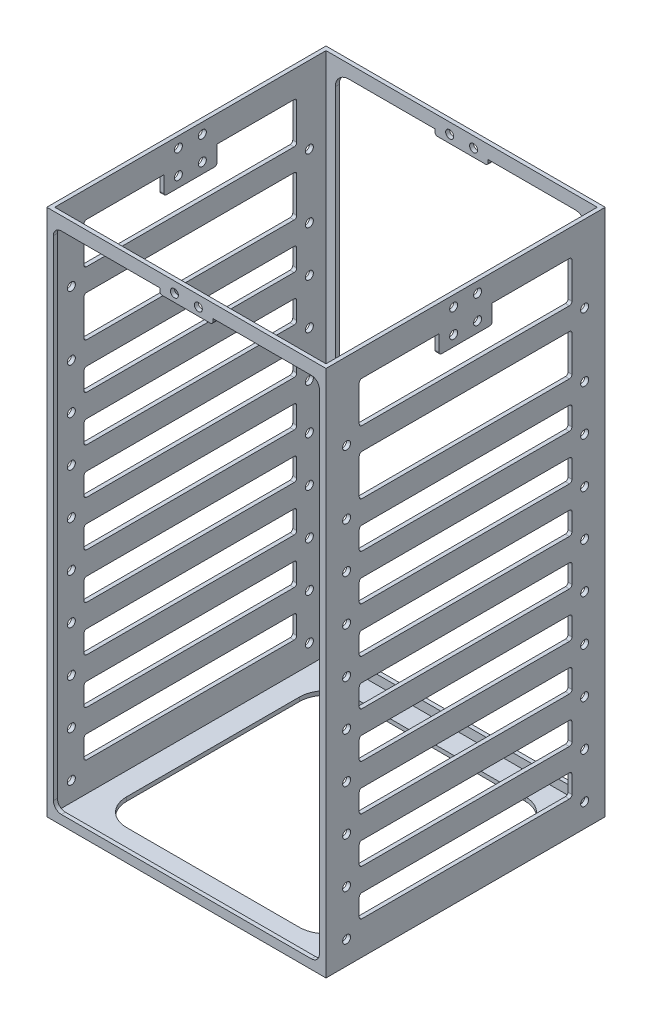
SolidWorks part; units mm, degrees
ref_plane "Front Plane" through (0, 0, 0) normal (0, 0, 1) x (1, 0, 0)
ref_plane "Top Plane" through (0, 0, 0) normal (0, 1, 0) x (1, 0, 0)
ref_plane "Right Plane" through (0, 0, 0) normal (1, 0, 0) x (0, 0, -1)
sketch "Sketch1" plane through (0, 0, 0) normal (0, 1, 0) x (1, 0, 0)
  line L1 (-52.5, -52.5) -> (52.5, -52.5)
  line L2 (-52.5, -52.5) -> (-52.5, 52.5)
  line L3 (-52.5, 52.5) -> (52.5, 52.5)
  line L4 (52.5, -52.5) -> (52.5, 52.5)
  line L5 (-52.5, -52.5) -> (52.5, 52.5) construction
  line L6 (-52.5, 52.5) -> (52.5, -52.5) construction
  line L7 (-32.5, -42.5) -> (32.5, -42.5)
  line L8 (-42.5, -32.5) -> (-42.5, 32.5)
  line L9 (-32.5, 42.5) -> (32.5, 42.5)
  line L10 (42.5, -32.5) -> (42.5, 32.5)
  line L11 (-42.5, -42.5) -> (42.5, 42.5) construction
  line L12 (-42.5, 42.5) -> (42.5, -42.5) construction
  arc A0 (32.5, -42.5) -> (42.5, -32.5) centre (32.5, -32.5) ccw
  arc A1 (32.5, 42.5) -> (42.5, 32.5) centre (32.5, 32.5) cw
  arc A2 (-42.5, 32.5) -> (-32.5, 42.5) centre (-32.5, 32.5) cw
  arc A3 (-32.5, -42.5) -> (-42.5, -32.5) centre (-32.5, -32.5) cw
  point P0 (0, 0)
  point P6 (0, 0)
  dimension "D3" = 10
  dimension "D1" = 105
  dimension "D2" = 42.5
extrude "Boss-Extrude2" add sketch "Sketch1" along normal blind 1.5 contours A3 L7 A0 L10 A1 L9 A2 L8 | L2 L1 L4 L3
sketch "Sketch3" plane through (0, 1.5, 0) normal (0, 1, 0) x (1, 0, 0)
  line L1 (-52.5, -52.5) -> (52.5, -52.5)
  line L2 (-52.5, -52.5) -> (-52.5, 52.5)
  line L3 (-52.5, 52.5) -> (52.5, 52.5)
  line L4 (52.5, -52.5) -> (52.5, 52.5)
  line L5 (-52.5, -52.5) -> (52.5, 52.5) construction
  line L6 (-52.5, 52.5) -> (52.5, -52.5) construction
  line L7 (-51, -51) -> (51, -51)
  line L8 (-51, -51) -> (-51, 51)
  line L9 (-51, 51) -> (51, 51)
  line L10 (51, -51) -> (51, 51)
  line L11 (-51, -51) -> (51, 51) construction
  line L12 (-51, 51) -> (51, -51) construction
  point P0 (0, 0)
  point P7 (0, 0)
  dimension "D1" = 1.5
extrude "Boss-Extrude3" add sketch "Sketch3" along normal blind 197 contours L8 L7 L10 L9 | L2 L3 L4 L1
sketch "Sketch4" plane through (0, 0, -52.5) normal (0, 0, 1) x (1, 0, 0)
  line L0 (-52.5, 0) -> (52.5, 0) construction
  line L1 (-42.5, 5) -> (42.5, 5)
  line L2 (-47.5, 10) -> (-47.5, 188.5)
  line L3 (-42.5, 193.5) -> (42.5, 193.5)
  line L4 (47.5, 10) -> (47.5, 188.5)
  line L5 (-47.5, 5) -> (47.5, 193.5) construction
  line L6 (-47.5, 193.5) -> (47.5, 5) construction
  line L7 (52.5, 198.5) -> (52.5, 0) construction
  line L8 (-51, 198.5) -> (51, 198.5) construction
  line L9 (-52.5, 198.5) -> (-52.5, 0) construction
  arc A0 (-42.5, 5) -> (-47.5, 10) centre (-42.5, 10) cw
  arc A1 (42.5, 5) -> (47.5, 10) centre (42.5, 10) ccw
  arc A2 (42.5, 193.5) -> (47.5, 188.5) centre (42.5, 188.5) cw
  arc A3 (-47.5, 188.5) -> (-42.5, 193.5) centre (-42.5, 188.5) cw
  point P0 (0, 99.25)
  dimension "D5" = 5
  dimension "D1" = 5
  dimension "D2" = 5
  dimension "D3" = 5
  dimension "D4" = 5
extrude "Cut-Extrude1" cut sketch "Sketch4" along normal up to surface (1.5 mm away) up to face at (0, 100, -51)
sketch "Sketch5" plane through (0, 0, 52.5) normal (0, 0, 1) x (1, 0, 0)
  line L0 (-52.5, 198.5) -> (52.5, 198.5) construction
  line L1 (-47, 3.5) -> (47, 3.5)
  line L2 (-50, 6.5) -> (-50, 190.5)
  line L3 (-47, 193.5) -> (47, 193.5)
  line L4 (50, 6.5) -> (50, 190.5)
  line L5 (-50, 3.5) -> (50, 193.5) construction
  line L6 (-50, 193.5) -> (50, 3.5) construction
  line L7 (-52.5, 1.5) -> (52.5, 1.5) construction
  line L8 (-52.5, 198.5) -> (-52.5, 0) construction
  line L9 (52.5, 198.5) -> (52.5, 0) construction
  arc A0 (47, 3.5) -> (50, 6.5) centre (47, 6.5) ccw
  arc A1 (-47, 3.5) -> (-50, 6.5) centre (-47, 6.5) cw
  arc A2 (47, 193.5) -> (50, 190.5) centre (47, 190.5) cw
  arc A3 (-50, 190.5) -> (-47, 193.5) centre (-47, 190.5) cw
  point P0 (0, 98.5)
  dimension "D5" = 3
  dimension "D1" = 5
  dimension "D2" = 2
  dimension "D3" = 2.5
  dimension "D4" = 2.5
sketch "Sketch6" plane through (52.5, 0, 0) normal (1, 0, 0) x (0, 0, -1)
  line L0 (-52.5, 3.5) -> (-52.5, 193.5) construction
  line L1 (52.5, 198.5) -> (52.5, 0) construction
  line L2 (-52.5, 0) -> (52.5, 0) construction
  circle A0 centre (-44.75, 8.75) radius 1.5
  circle A1 centre (44.75, 8.75) radius 1.5
  circle A2 centre (-44.75, 25.85) radius 1.5
  circle A3 centre (44.75, 25.85) radius 1.5
  circle A4 centre (-44.75, 42.95) radius 1.5
  circle A5 centre (44.75, 42.95) radius 1.5
  circle A6 centre (-44.75, 60.05) radius 1.5
  circle A7 centre (44.75, 60.05) radius 1.5
  circle A8 centre (-44.75, 77.15) radius 1.5
  circle A9 centre (44.75, 77.15) radius 1.5
  circle A10 centre (-44.75, 94.25) radius 1.5
  circle A11 centre (44.75, 94.25) radius 1.5
  circle A12 centre (-44.75, 111.35) radius 1.5
  circle A13 centre (44.75, 111.35) radius 1.5
  circle A14 centre (-44.75, 128.45) radius 1.5
  circle A15 centre (44.75, 128.45) radius 1.5
  circle A16 centre (-44.75, 145.55) radius 1.5
  circle A17 centre (44.75, 145.55) radius 1.5
  circle A18 centre (-44.75, 169.55) radius 1.5
  circle A19 centre (44.75, 169.55) radius 1.5
  dimension "D4" = 3
  dimension "D5" = 3
  dimension "D1" = 7.75
  dimension "D2" = 7.75
  dimension "D3" = 8.75
  dimension "D7" = 17.1
  dimension "D9" = 24
  dimension "D6" = 9
  dimension "D8" = 2
extrude "Cut-Extrude2" cut sketch "Sketch6" against normal through all
extrude "Cut-Extrude3" cut sketch "Sketch5" against normal up to surface (1.5 mm away) up to face at (0, 100, 51)
sketch "Sketch7" plane through (52.5, 0, 0) normal (1, 0, 0) x (0, 0, -1)
  line L0 (-40, 30.65) -> (-40, 37.15)
  line L1 (-39, 12.55) -> (39, 12.55)
  line L2 (-40, 13.55) -> (-40, 20.05)
  line L3 (-39, 21.05) -> (39, 21.05)
  line L4 (40, 13.55) -> (40, 20.05)
  line L5 (-40, 12.55) -> (40, 21.05) construction
  line L6 (-40, 21.05) -> (40, 12.55) construction
  line L7 (52.5, 198.5) -> (52.5, 0) construction
  line L8 (-39, 29.65) -> (39, 29.65)
  line L9 (40, 30.65) -> (40, 37.15)
  line L10 (-39, 38.15) -> (39, 38.15)
  line L11 (-40, 47.75) -> (-40, 54.25)
  line L12 (-39, 46.75) -> (39, 46.75)
  line L13 (40, 47.75) -> (40, 54.25)
  line L14 (-39, 55.25) -> (39, 55.25)
  line L15 (-40, 64.85) -> (-40, 71.35)
  line L16 (-39, 63.85) -> (39, 63.85)
  line L17 (40, 64.85) -> (40, 71.35)
  line L18 (-39, 72.35) -> (39, 72.35)
  line L19 (-40, 81.95) -> (-40, 88.45)
  line L20 (-39, 80.95) -> (39, 80.95)
  line L21 (40, 81.95) -> (40, 88.45)
  line L22 (-39, 89.45) -> (39, 89.45)
  line L23 (-40, 99.05) -> (-40, 105.55)
  line L24 (-39, 98.05) -> (39, 98.05)
  line L25 (40, 99.05) -> (40, 105.55)
  line L26 (-39, 106.55) -> (39, 106.55)
  line L27 (-40, 116.15) -> (-40, 122.65)
  line L28 (-39, 115.15) -> (39, 115.15)
  line L29 (40, 116.15) -> (40, 122.65)
  line L30 (-39, 123.65) -> (39, 123.65)
  line L31 (-40, 133.25) -> (-40, 139.75)
  line L32 (-39, 132.25) -> (39, 132.25)
  line L33 (40, 133.25) -> (40, 139.75)
  line L34 (-39, 140.75) -> (39, 140.75)
  circle A0 centre (-44.75, 8.75) radius 1.5 construction
  arc A1 (39, 21.05) -> (40, 20.05) centre (39, 20.05) cw
  arc A2 (39, 12.55) -> (40, 13.55) centre (39, 13.55) ccw
  arc A3 (-39, 12.55) -> (-40, 13.55) centre (-39, 13.55) cw
  arc A4 (-40, 20.05) -> (-39, 21.05) centre (-39, 20.05) cw
  arc A5 (-40, 37.15) -> (-39, 38.15) centre (-39, 37.15) cw
  arc A6 (-39, 29.65) -> (-40, 30.65) centre (-39, 30.65) cw
  arc A7 (39, 29.65) -> (40, 30.65) centre (39, 30.65) ccw
  arc A8 (39, 38.15) -> (40, 37.15) centre (39, 37.15) cw
  arc A9 (-40, 54.25) -> (-39, 55.25) centre (-39, 54.25) cw
  arc A10 (-39, 46.75) -> (-40, 47.75) centre (-39, 47.75) cw
  arc A11 (39, 46.75) -> (40, 47.75) centre (39, 47.75) ccw
  arc A12 (39, 55.25) -> (40, 54.25) centre (39, 54.25) cw
  arc A13 (-40, 71.35) -> (-39, 72.35) centre (-39, 71.35) cw
  arc A14 (-39, 63.85) -> (-40, 64.85) centre (-39, 64.85) cw
  arc A15 (39, 63.85) -> (40, 64.85) centre (39, 64.85) ccw
  arc A16 (39, 72.35) -> (40, 71.35) centre (39, 71.35) cw
  arc A17 (-40, 88.45) -> (-39, 89.45) centre (-39, 88.45) cw
  arc A18 (-39, 80.95) -> (-40, 81.95) centre (-39, 81.95) cw
  arc A19 (39, 80.95) -> (40, 81.95) centre (39, 81.95) ccw
  arc A20 (39, 89.45) -> (40, 88.45) centre (39, 88.45) cw
  arc A21 (-40, 105.55) -> (-39, 106.55) centre (-39, 105.55) cw
  arc A22 (-39, 98.05) -> (-40, 99.05) centre (-39, 99.05) cw
  arc A23 (39, 98.05) -> (40, 99.05) centre (39, 99.05) ccw
  arc A24 (39, 106.55) -> (40, 105.55) centre (39, 105.55) cw
  arc A25 (-40, 122.65) -> (-39, 123.65) centre (-39, 122.65) cw
  arc A26 (-39, 115.15) -> (-40, 116.15) centre (-39, 116.15) cw
  arc A27 (39, 115.15) -> (40, 116.15) centre (39, 116.15) ccw
  arc A28 (39, 123.65) -> (40, 122.65) centre (39, 122.65) cw
  arc A29 (-40, 139.75) -> (-39, 140.75) centre (-39, 139.75) cw
  arc A30 (-39, 132.25) -> (-40, 133.25) centre (-39, 133.25) cw
  arc A31 (39, 132.25) -> (40, 133.25) centre (39, 133.25) ccw
  arc A32 (39, 140.75) -> (40, 139.75) centre (39, 139.75) cw
  point P0 (0, 16.8)
  dimension "D5" = 1
  dimension "D1" = 8.5
  dimension "D2" = 3.8
  dimension "D3" = 80
  dimension "D4" = 12.5
  dimension "D7" = 8.6
  dimension "D6" = 8
extrude "Cut-Extrude4" cut sketch "Sketch7" against normal through all
sketch "Sketch8" plane through (52.5, 0, 0) normal (1, 0, 0) x (0, 0, -1)
  line L1 (-39, 149.35) -> (39, 149.35)
  line L2 (-40, 150.35) -> (-40, 163.75)
  line L3 (-39, 164.75) -> (39, 164.75)
  line L4 (40, 150.35) -> (40, 163.75)
  line L5 (-40, 149.35) -> (40, 164.75) construction
  line L6 (-40, 164.75) -> (40, 149.35) construction
  line L7 (52.5, 198.5) -> (52.5, 0) construction
  line L8 (-40, 188.55) -> (40, 173.15) construction
  line L9 (-40, 174.15) -> (-40, 187.55)
  line L10 (-39, 173.15) -> (39, 173.15)
  line L11 (40, 174.15) -> (40, 187.55)
  line L12 (-39, 188.55) -> (39, 188.55)
  circle A0 centre (-44.75, 145.55) radius 1.5 construction
  arc A2 (-40, 163.75) -> (-39, 164.75) centre (-39, 163.75) cw
  arc A3 (39, 164.75) -> (40, 163.75) centre (39, 163.75) cw
  arc A4 (39, 149.35) -> (40, 150.35) centre (39, 150.35) ccw
  arc A5 (-39, 149.35) -> (-40, 150.35) centre (-39, 150.35) cw
  arc A6 (-39, 173.15) -> (-40, 174.15) centre (-39, 174.15) cw
  arc A7 (-40, 187.55) -> (-39, 188.55) centre (-39, 187.55) cw
  arc A8 (39, 173.15) -> (40, 174.15) centre (39, 174.15) ccw
  arc A9 (39, 188.55) -> (40, 187.55) centre (39, 187.55) cw
  point P0 (0, 157.05)
  dimension "D5" = 1
  dimension "D1" = 3.8
  dimension "D2" = 15.4
  dimension "D3" = 80
  dimension "D4" = 12.5
  dimension "D7" = 8.4
  dimension "D6" = 2
extrude "Cut-Extrude5" cut sketch "Sketch8" against normal through all
sketch "Sketch15" plane through (52.5, 0, 0) normal (1, 0, 0) x (0, 0, -1)
  line L0 (39, 188.55) -> (-39, 188.55) construction
  line L1 (-10, 188.55) -> (10, 188.55)
  line L2 (-10, 188.55) -> (-10, 182.55)
  line L3 (-9, 181.55) -> (9, 181.55)
  line L4 (10, 188.55) -> (10, 182.55)
  line L5 (-52.5, 198.5) -> (-52.5, 0) construction
  arc A0 (9, 181.55) -> (10, 182.55) centre (9, 182.55) ccw
  arc A1 (-10, 182.55) -> (-9, 181.55) centre (-9, 182.55) ccw
  dimension "D4" = 1
  dimension "D1" = 20
  dimension "D2" = 7
  dimension "D3" = 42.5
extrude "Boss-Extrude4" add sketch "Sketch15" against normal up to surface (1.5 mm away) up to face at (51, 157.05, 0)
sketch "Sketch16" plane through (-52.5, 0, 0) normal (-1, 0, 0) x (0, 0, 1)
  line L1 (-10, 188.55) -> (10, 188.55)
  line L2 (-10, 188.55) -> (-10, 182.55)
  line L3 (-9, 181.55) -> (9, 181.55)
  line L4 (10, 188.55) -> (10, 182.55)
  arc A0 (9, 181.55) -> (10, 182.55) centre (9, 182.55) ccw
  arc A1 (-10, 182.55) -> (-9, 181.55) centre (-9, 182.55) ccw
  dimension "D3" = 1
  dimension "D1" = 7
  dimension "D2" = 20
extrude "Boss-Extrude5" add sketch "Sketch16" against normal up to surface (1.5 mm away) up to face at (-51, 157.05, 0)
sketch "Sketch9" plane through (52.5, 0, 0) normal (1, 0, 0) x (0, 0, -1)
  line L0 (-52.5, 198.5) -> (52.5, 198.5) construction
  line L1 (-52.5, 198.5) -> (-52.5, 0) construction
  line L2 (-10.0428, 190) -> (10.2919, 190) construction
  circle A0 centre (-4.5, 194.5) radius 1.5
  circle A1 centre (4.5, 194.5) radius 1.5
  circle A2 centre (4.5, 185.5) radius 1.5
  circle A3 centre (-4.5, 185.5) radius 1.5
  dimension "D1" = 3
  dimension "D3" = 9
  dimension "D5" = 3
  dimension "D2" = 4
  dimension "D4" = 48
  dimension "D6" = 4.5
extrude "Cut-Extrude6" cut sketch "Sketch9" against normal through all
sketch "Sketch17" plane through (0, 0, 52.5) normal (0, 0, 1) x (1, 0, 0)
  line L0 (47, 193.5) -> (-47, 193.5) construction
  line L1 (-10, 193.5) -> (10, 193.5)
  line L2 (-10, 193.5) -> (-10, 192.5)
  line L3 (-9, 191.5) -> (9, 191.5)
  line L4 (10, 193.5) -> (10, 192.5)
  line L5 (-52.5, 198.5) -> (-52.5, 0) construction
  arc A0 (9, 191.5) -> (10, 192.5) centre (9, 192.5) ccw
  arc A1 (-10, 192.5) -> (-9, 191.5) centre (-9, 192.5) ccw
  dimension "D4" = 1
  dimension "D1" = 20
  dimension "D2" = 42.5
  dimension "D3" = 2
extrude "Boss-Extrude6" add sketch "Sketch17" against normal up to surface (1.5 mm away) up to face at (0, 98.5, 51)
sketch "Sketch18" plane through (0, 0, -52.5) normal (0, 0, -1) x (-1, 0, 0)
  line L1 (-10, 193.5) -> (10, 193.5)
  line L2 (-10, 193.5) -> (-10, 192.5)
  line L3 (-9, 191.5) -> (9, 191.5)
  line L4 (10, 193.5) -> (10, 192.5)
  arc A0 (9, 191.5) -> (10, 192.5) centre (9, 192.5) ccw
  arc A1 (-10, 192.5) -> (-9, 191.5) centre (-9, 192.5) ccw
  dimension "D3" = 1
  dimension "D1" = 2
  dimension "D2" = 20
extrude "Boss-Extrude7" add sketch "Sketch18" against normal up to surface (1.5 mm away) up to face at (0, 99.25, -51)
sketch "Sketch19" plane through (0, 0, 52.5) normal (0, 0, 1) x (1, 0, 0)
  line L0 (0, 198.5) -> (0, 191.5) construction
  line L1 (-9, 191.5) -> (9, 191.5) construction
  line L3 (-52.5, 198.5) -> (52.5, 198.5) construction
  circle A0 centre (-4.5, 194.5) radius 1.5
  circle A1 centre (4.5, 194.5) radius 1.5
  dimension "D1" = 3
  dimension "D2" = 4
  dimension "D3" = 4.5
extrude "Cut-Extrude7" cut sketch "Sketch19" against normal through all
